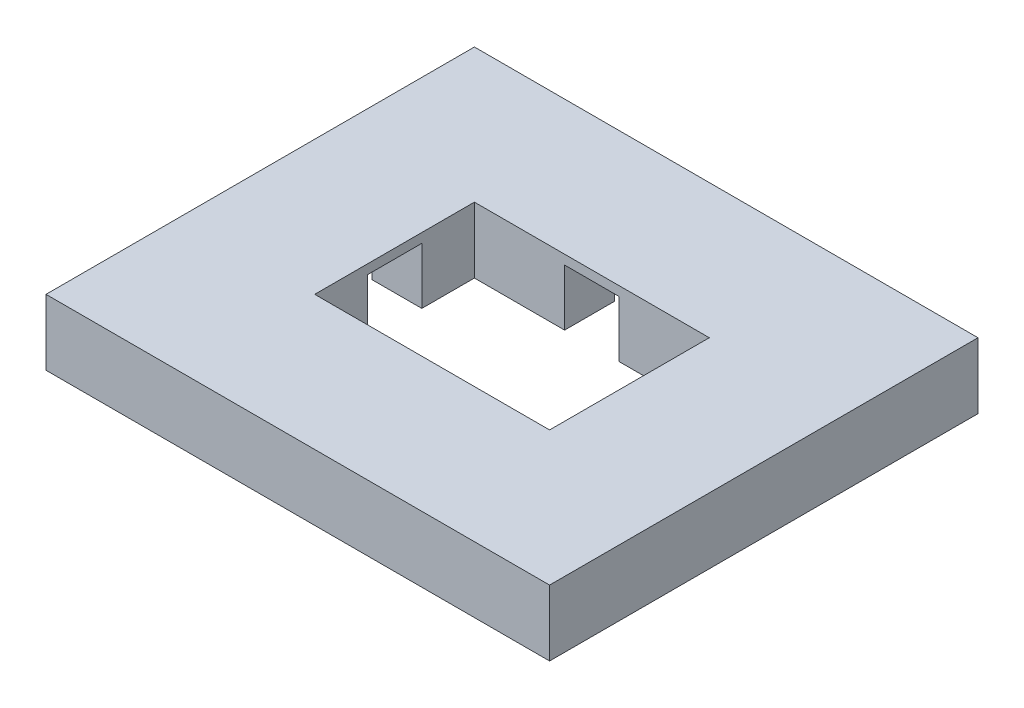
SolidWorks part; units mm, degrees
ref_plane "Front Plane" through (0, 0, 0) normal (0, 0, 1) x (1, 0, 0)
ref_plane "Top Plane" through (0, 0, 0) normal (0, 1, 0) x (1, 0, 0)
ref_plane "Right Plane" through (0, 0, 0) normal (1, 0, 0) x (0, 0, -1)
sketch "Sketch1" plane through (0, 0, 0) normal (0, 1, 0) x (1, 0, 0)
  line L0 (-26.8, 22.8) -> (26.8, 22.8)
  line L1 (-11.8, -7.8) -> (11.8, -7.8)
  line L2 (-11.8, -7.8) -> (-11.8, 7.8)
  line L3 (-11.8, 7.8) -> (11.8, 7.8)
  line L4 (11.8, -7.8) -> (11.8, 7.8)
  line L5 (-11.8, -7.8) -> (11.8, 7.8) construction
  line L6 (-11.8, 7.8) -> (11.8, -7.8) construction
  line L7 (26.8, -22.8) -> (26.8, 22.8)
  line L8 (-26.8, -22.8) -> (26.8, -22.8)
  line L9 (-26.8, -22.8) -> (-26.8, 22.8)
  point P0 (0, 0)
  dimension "D1" = 23.6
  dimension "D2" = 15.6
  dimension "D3" = 15
extrude "Boss-Extrude1" add sketch "Sketch1" along normal blind 6
sketch "Sketch2" plane through (0, 0, 0) normal (0, -1, 0) x (1, 0, 0)
  line L4 (-26.8, 22.8) -> (-26.8, -22.8)
  line L5 (-26.8, -22.8) -> (26.8, -22.8)
  line L6 (26.8, -22.8) -> (26.8, 22.8)
  line L7 (26.8, 22.8) -> (-26.8, 22.8)
  line L8 (-26.8, 22.8) -> (-26.8, -22.8)
  line L9 (-26.8, -22.8) -> (26.8, -22.8)
  line L10 (26.8, -22.8) -> (26.8, 22.8)
  line L11 (26.8, 22.8) -> (-26.8, 22.8)
  dimension "D1" = 0
sketch "Sketch4" plane through (0, 0, 0) normal (0, -1, 0) x (1, 0, 0)
  line L0 (11.8, -7.8) -> (-11.8, -7.8) construction
  line L1 (2.9, -18.8) -> (-2.9, -18.8)
  line L2 (2.9, -18.8) -> (2.9, 18.8)
  line L3 (2.9, 18.8) -> (-2.9, 18.8)
  line L4 (-2.9, -18.8) -> (-2.9, 18.8)
  line L5 (2.9, -18.8) -> (-2.9, 18.8) construction
  line L6 (2.9, 18.8) -> (-2.9, -18.8) construction
  line L8 (11.8, 7.8) -> (11.8, -7.8) construction
  line L9 (-22.8, -2.9) -> (22.8, -2.9)
  line L10 (-22.8, -2.9) -> (-22.8, 2.9)
  line L11 (-22.8, 2.9) -> (22.8, 2.9)
  line L12 (22.8, -2.9) -> (22.8, 2.9)
  line L13 (-22.8, -2.9) -> (22.8, 2.9) construction
  line L14 (-22.8, 2.9) -> (22.8, -2.9) construction
  point P0 (0, 0)
  point P8 (0, 0)
  line M9 (-11.8, 7.8) -> (11.8, 7.8)
  line M10 (11.8, 7.8) -> (11.8, -7.8)
  line M11 (11.8, -7.8) -> (-11.8, -7.8)
  line M12 (-11.8, -7.8) -> (-11.8, 7.8)
  dimension "D1" = 11
  dimension "D2" = 5.8
  dimension "D3" = 11
  dimension "D4" = 5.8
extrude "Cut-Extrude1" cut sketch "Sketch4" against normal blind 5 contours L11 L10 L9 M12 | L4 L1 L2 M11 | L4 L2 L3 M9 | L9 L12 L11 M10
sketch "Sketch5" plane through (0, 0, 0) normal (0, -1, 0) x (1, 0, 0)
  line L0 (-2.9, -18.8) -> (-22.8, -18.8)
  line L1 (-22.8, -18.8) -> (-22.8, -2.9)
  line L2 (-2.9, -13.8) -> (-17.8, -13.8)
  line L3 (-17.8, -13.8) -> (-17.8, -2.9)
  line L4 (-2.9, -18.8) -> (-2.9, -13.8)
  line L5 (-22.8, -2.9) -> (-17.8, -2.9)
  line L6 (-32.6665, 0) -> (37.445, 0) construction
  line L7 (0, -36.0556) -> (0, 52.8908) construction
  line L8 (-2.9, 18.8) -> (-2.9, 13.8)
  line L9 (-2.9, 13.8) -> (-17.8, 13.8)
  line L10 (-22.8, 2.9) -> (-17.8, 2.9)
  line L11 (-17.8, 13.8) -> (-17.8, 2.9)
  line L12 (-22.8, 18.8) -> (-22.8, 2.9)
  line L13 (-2.9, 18.8) -> (-22.8, 18.8)
  line L14 (22.8, -18.8) -> (22.8, -2.9)
  line L15 (22.8, -2.9) -> (17.8, -2.9)
  line L16 (17.8, -13.8) -> (17.8, -2.9)
  line L17 (2.9, -13.8) -> (17.8, -13.8)
  line L18 (2.9, -18.8) -> (22.8, -18.8)
  line L19 (2.9, -18.8) -> (2.9, -13.8)
  line L20 (2.9, 18.8) -> (2.9, 13.8)
  line L21 (2.9, 18.8) -> (22.8, 18.8)
  line L22 (2.9, 13.8) -> (17.8, 13.8)
  line L23 (17.8, 13.8) -> (17.8, 2.9)
  line L24 (22.8, 18.8) -> (22.8, 2.9)
  line L25 (22.8, 2.9) -> (17.8, 2.9)
  dimension "D1" = 5
extrude "Cut-Extrude2" cut sketch "Sketch5" against normal blind 5
sketch "Sketch6" plane through (0, 0, 0) normal (0, -1, 0) x (1, 0, 0)
  line L1 (-22.8, -18.8) -> (-28.8373, -18.8)
  line L2 (-22.8, -18.8) -> (-22.8, -6.7529)
  line L3 (-22.8, -6.7529) -> (-28.8373, -6.7529)
  line L4 (-28.8373, -18.8) -> (-28.8373, -6.7529)
extrude "Cut-Extrude3" cut sketch "Sketch6" against normal blind 5
sketch "Sketch7" plane through (0, 0, 0) normal (0, -1, 0) x (1, 0, 0)
  line L6 (-17.8, -2.9) -> (-17.8, -13.8)
  line L7 (-17.8, -13.8) -> (-2.9, -13.8)
  line L8 (-2.9, -13.8) -> (-2.9, -7.8)
  line L9 (-2.9, -7.8) -> (-11.8, -7.8)
  line L10 (22.8, -18.8) -> (-26.8, -18.8)
  line L11 (-26.8, -18.8) -> (-26.8, -22.8)
  line L12 (-26.8, -22.8) -> (26.8, -22.8)
  line L13 (26.8, -22.8) -> (26.8, 22.8)
  line L14 (26.8, 22.8) -> (-26.8, 22.8)
  line L15 (-26.8, 22.8) -> (-26.8, -6.7529)
  line L16 (-26.8, -6.7529) -> (-22.8, -6.7529)
  line L17 (-22.8, -6.7529) -> (-22.8, 18.8)
  line L18 (-22.8, 18.8) -> (22.8, 18.8)
  line L19 (22.8, 18.8) -> (22.8, -18.8)
  line L20 (22.8, -18.8) -> (-26.8, -18.8)
  line L21 (-26.8, -18.8) -> (-26.8, -22.8)
  line L22 (-26.8, -22.8) -> (26.8, -22.8)
  line L23 (26.8, -22.8) -> (26.8, 22.8)
  line L24 (26.8, 22.8) -> (-26.8, 22.8)
  line L25 (-26.8, 22.8) -> (-26.8, -6.7529)
  line L26 (-26.8, -6.7529) -> (-22.8, -6.7529)
  line L27 (-22.8, -6.7529) -> (-22.8, 18.8)
  line L28 (-22.8, 18.8) -> (22.8, 18.8)
  line L29 (22.8, 18.8) -> (22.8, -18.8)
  line L30 (-11.8, -7.8) -> (-11.8, -2.9)
  line L31 (-11.8, -2.9) -> (-17.8, -2.9)
  line L32 (-17.8, -2.9) -> (-17.8, -13.8)
  line L33 (-17.8, -13.8) -> (-2.9, -13.8)
  line L34 (-2.9, -13.8) -> (-2.9, -7.8)
  line L35 (-2.9, -7.8) -> (-11.8, -7.8)
  line L36 (-11.8, -7.8) -> (-11.8, -2.9)
  line L37 (-11.8, -2.9) -> (-17.8, -2.9)
  line L38 (-2.9, 13.8) -> (-17.8, 13.8)
  line L39 (-17.8, 13.8) -> (-17.8, 2.9)
  line L40 (-17.8, 2.9) -> (-11.8, 2.9)
  line L41 (-11.8, 2.9) -> (-11.8, 7.8)
  line L42 (-11.8, 7.8) -> (-2.9, 7.8)
  line L43 (-2.9, 7.8) -> (-2.9, 13.8)
  line L44 (-2.9, 13.8) -> (-17.8, 13.8)
  line L45 (-17.8, 13.8) -> (-17.8, 2.9)
  line L46 (-17.8, 2.9) -> (-11.8, 2.9)
  line L47 (-11.8, 2.9) -> (-11.8, 7.8)
  line L48 (-11.8, 7.8) -> (-2.9, 7.8)
  line L49 (-2.9, 7.8) -> (-2.9, 13.8)
  line L50 (2.9, -13.8) -> (17.8, -13.8)
  line L51 (17.8, -13.8) -> (17.8, -2.9)
  line L52 (17.8, -2.9) -> (11.8, -2.9)
  line L53 (11.8, -2.9) -> (11.8, -7.8)
  line L54 (11.8, -7.8) -> (2.9, -7.8)
  line L55 (2.9, -7.8) -> (2.9, -13.8)
  line L56 (2.9, -13.8) -> (17.8, -13.8)
  line L57 (17.8, -13.8) -> (17.8, -2.9)
  line L58 (17.8, -2.9) -> (11.8, -2.9)
  line L59 (11.8, -2.9) -> (11.8, -7.8)
  line L60 (11.8, -7.8) -> (2.9, -7.8)
  line L61 (2.9, -7.8) -> (2.9, -13.8)
  line L62 (17.8, 2.9) -> (17.8, 13.8)
  line L63 (17.8, 13.8) -> (2.9, 13.8)
  line L64 (2.9, 13.8) -> (2.9, 7.8)
  line L65 (2.9, 7.8) -> (11.8, 7.8)
  line L66 (11.8, 7.8) -> (11.8, 2.9)
  line L67 (11.8, 2.9) -> (17.8, 2.9)
  line L68 (17.8, 2.9) -> (17.8, 13.8)
  line L69 (17.8, 13.8) -> (2.9, 13.8)
  line L70 (2.9, 13.8) -> (2.9, 7.8)
  line L71 (2.9, 7.8) -> (11.8, 7.8)
  line L72 (11.8, 7.8) -> (11.8, 2.9)
  line L73 (11.8, 2.9) -> (17.8, 2.9)
  dimension "D1" = 0
  dimension "D2" = 0
  dimension "D3" = 0
  dimension "D4" = 0
  dimension "D5" = 0
extrude "Boss-Extrude3" add sketch "Sketch7" along normal blind 1
sketch "Sketch8" plane through (0, 6, 0) normal (0, 1, 0) x (1, 0, 0)
  line L1 (-12.5, 8.5) -> (12.5, 8.5)
  line L2 (-12.5, 8.5) -> (-12.5, -8.5)
  line L3 (-12.5, -8.5) -> (12.5, -8.5)
  line L4 (12.5, 8.5) -> (12.5, -8.5)
  line L5 (-12.5, 8.5) -> (12.5, -8.5) construction
  line L6 (-12.5, -8.5) -> (12.5, 8.5) construction
  point P0 (0, 0)
  dimension "D1" = 17
  dimension "D2" = 25
extrude "Cut-Extrude4" cut sketch "Sketch8" against normal through all
